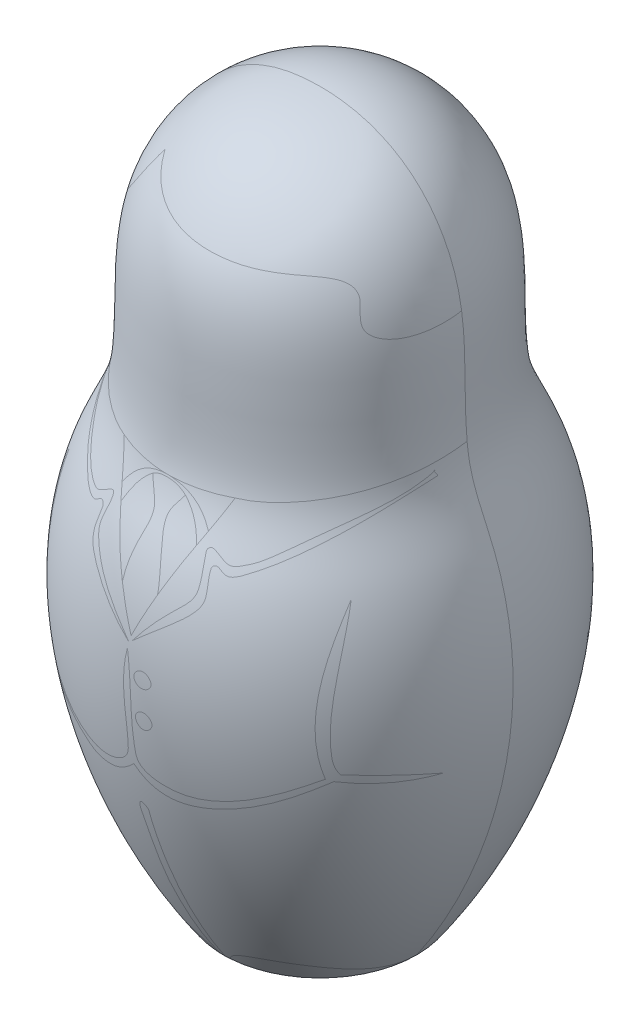
SolidWorks part; units mm, degrees
ref_plane "Plan de face" through (0, 0, 0) normal (0, 0, 1) x (1, 0, 0)
ref_plane "Plan de dessus" through (0, 0, 0) normal (0, 1, 0) x (1, 0, 0)
ref_plane "Plan de droite" through (0, 0, 0) normal (1, 0, 0) x (0, 0, -1)
sketch "Esquisse1" plane through (0, 0, 0) normal (0, 0, 1) x (1, 0, 0)
  line L0 (129.3492, 447.0549) -> (1494.8504, 447.0549) construction
  line L1 (0, 0) -> (0, 471.5) construction
  line L2 (0, 0) -> (-150.0296, 0) construction
  line L3 (0, 0) -> (0, 471.5)
  line L4 (0, 471.5) -> (-60.3699, 471.5) construction
  spline S0 degree 3 poles (0, 0) (-21.7271, 0) (-42.9654, 1.2949) (-63.75, 8) knots 0 0 0 0 1 1 1 1
  spline S1 degree 3 poles (-63.75, 8) (-110.6212, 75.097) (-153.2976, 197.1961) (-99.027, 296.1163) (-93.8746, 343.1344) (-100.8408, 417.717) (-51.4988, 471.5) (0, 471.5) knots 0 0 0 0 0.516513 0.585577 0.634733 0.784867 1 1 1 1
  dimension "D1" = 471.5
  dimension "D2" = 180.75
  dimension "D3" = 192.5
  dimension "D4" = 200
  dimension "D5" = 227.5
  dimension "D6" = 251
  dimension "D7" = 127.5
  dimension "D8" = 73
  dimension "D9" = 2
  dimension "D10" = 8
  dimension "D11" = 166
  dimension "D12" = 266.5
  dimension "D13" = 300
  dimension "D14" = 325.5
  dimension "D15" = 404
revolve "Révolution1" add sketch "Esquisse1" angle 360 about L3
ref_plane "Plan1" through (0, 0, 127) normal (0, 0, 1) x (1, 0, 0)
split line "Ligne de séparation3"
sketch "Esquisse3" plane through (0, 0, 127) normal (0, 0, 1) x (1, 0, 0)
  line L0 (129.3333, 447) -> (1494.6667, 447) construction
sketch3d "Esquisse3D3"
  arc A0 (63.75, 8, 0) -> (-63.75, 8, 0) centre (0, 8, 0) ccw construction
  arc A1 (63.75, 8, 0) -> (-63.75, 8, 0) centre (0, 8, 0) ccw construction
  arc A3 (63.75, 8, 0) -> (-63.75, 8, 0) centre (0, 8, 0) ccw construction
  point P0 (-63.75, 8, 0)
  point P1 (-96.5924, 320.5694, 0)
  point P2 (2.1214, 219.2703, 125.7318)
  point P3 (96.8721, 317.4915, 0)
  point P4 (-34.896, 21.9314, 64.092)
  point P5 (-3.421, 8, 63.6581)
  point P6 (4.545, 8, 63.5878)
  point P10 (0, -55.75, 0)
  point P11 (22.5504, 20.4053, 68.3902)
  point P15 (0, -55.75, 0)
  point P16 (47.011, 20.9144, 54.9755)
  point P17 (0.2994, 121.5679, 116.8557)
  point P18 (63.75, 8, 0)
  point P19 (63.75, 8, 0)
  point P20 (0, 471.5, 0)
  point P21 (-63.75, 8, 0)
  point P22 (0, 471.5, 0)
  point P23 (3.0312, 118.8634, 116.071)
  point P24 (3.0501, 97.6958, 109.3976)
  point P25 (1.0881, 8, 63.7407)
  point P29 (0, -55.75, 0)
  point P30 (10.0561, 182.4435, 126.4628)
  point P31 (-1.9324, 8, 63.7207)
  point P32 (-3.027, 55.1714, 91.4879)
  point P33 (-2.1547, 120.0749, 116.4276)
  point P34 (-1.1624, 121.5882, 116.8558)
  point P35 (15.0074, 177.836, 125.6951)
  point P36 (9.4058, 205.7294, 126.5297)
  point P37 (14.9379, 200.5466, 126.2001)
  point P38 (9.4931, 196.0044, 126.8041)
  point P39 (4.3686, 200.5757, 127.0052)
  point P40 (9.2308, 172.1282, 125.7929)
  point P41 (4.8984, 177.8704, 126.4954)
  point P42 (-35.9744, 301.2891, 92.9311)
  point P43 (1.0637, 221.52, 125.4694)
  point P44 (36.7481, 301.3439, 92.6125)
  point P45 (32.1198, 254.5054, 113.7083)
  point P46 (-72.4286, 286.5685, 75.8176)
  point P47 (-48.3809, 271.6775, 100.4855)
  point P48 (-43.1357, 271.6331, 102.8677)
  point P49 (-31.5697, 277.1148, 104.4017)
  point P50 (-31.0007, 274.5668, 105.7802)
  point P51 (-33.4455, 257.9423, 112.1193)
  point P52 (-0.2086, 217.8373, 125.9117)
  point P53 (-96.1025, 306.9029, 21.0637)
  point P54 (31.0306, 275.6136, 105.2762)
  point P55 (-34.9169, 249.4975, 114.492)
  point P56 (-37.0738, 256.8402, 111.3728)
  point P57 (-35.7203, 268.5841, 107.0736)
  point P58 (-37.4321, 269.8978, 105.8866)
  point P59 (-42.0501, 267.5888, 105.2041)
  point P60 (-50.3305, 267.6685, 101.4661)
  point P61 (32.9944, 276.9354, 104.046)
  point P62 (43.9841, 271.3084, 102.6642)
  point P63 (49.4223, 272.5547, 99.5414)
  point P64 (95.6123, 310.2258, 20.5768)
  point P65 (96.5144, 307.1724, 18.8202)
  point P66 (76.0684, 285.9788, 72.5308)
  point P67 (-95.7627, 308.1062, 21.5604)
  point P68 (48.0665, 267.0958, 102.8228)
  point P69 (42.7328, 266.8377, 105.2673)
  point P70 (36.969, 269.5906, 106.1905)
  point P71 (35.7797, 268.5972, 107.0479)
  point P72 (36.9226, 256.2794, 111.6232)
  point P73 (-0.5316, 214.1387, 126.2817)
  point P74 (-2.9218, 152.4546, 123.5713)
  point P75 (-19.5628, 140.5771, 119.8137)
  point P76 (-36.8841, 140.7008, 115.6883)
  point P77 (-91.5548, 164.8891, 85.6471)
  point P78 (-88.4673, 188.3172, 91.2377)
  point P79 (-90.8697, 227.8129, 85.196)
  point P80 (-90.8108, 257.9744, 73.7572)
  point P81 (-94.8912, 229.0429, 80.3789)
  point P82 (-93.1332, 198.5233, 86.5304)
  point P83 (-94.2344, 169.677, 83.4845)
  point P84 (-118.1077, 158.7426, 39.5987)
  point P85 (-94.1807, 163.7553, 82.5428)
  point P86 (-107.1053, 160.578, 64.1034)
  point P87 (19.9549, 134.8812, 118.4994)
  point P88 (36.5383, 135.6973, 114.6707)
  point P89 (92.9702, 163.2971, 83.8192)
  point P90 (-34.2098, 134.8647, 115.1916)
  point P91 (-31.9633, 134.3334, 115.7098)
  point P92 (-0.0302, 146.4869, 122.56)
  point P93 (104.7576, 160.131, 67.7606)
  point P94 (118.7156, 157.8779, 37.3259)
  point P95 (107.0656, 164.6096, 65.1636)
  point P96 (95.3607, 167.4122, 81.831)
  point P97 (93.3611, 176.9477, 85.3951)
  point P98 (93.708, 209.643, 85.1902)
  point P99 (91.7691, 260.4043, 71.1524)
  point P100 (88.6538, 210.467, 90.3559)
  point P101 (90.397, 164.9225, 86.8739)
  point P102 (38.2347, 141.3961, 115.3991)
  point P103 (19.7174, 141.378, 119.9549)
  point P104 (2.8199, 151.9842, 123.4958)
  point P105 (2.0868, 194.6854, 127.1473)
split line "Ligne de séparation8"
sketch3d "Esquisse3D4"
  point P0 (-24.3333, 276.1453, 106.7746)
  point P1 (-10.0408, 296.0562, 100.7119)
  point P3 (28.8345, 283.3201, 102.2791)
  point P4 (-35.9744, 301.2891, 92.9311)
  point P5 (1.0637, 221.52, 125.4694)
  point P6 (-35.9744, 301.2891, 92.9311)
  point P7 (1.0637, 221.52, 125.4694)
  point P8 (0.3697, 298.7748, 100.3528)
  point P9 (12.8279, 294.4565, 100.948)
  point P10 (25.36, 275.6775, 106.7542)
  point P11 (1.0637, 221.52, 125.4694)
  point P12 (36.7481, 301.3439, 92.6125)
  point P13 (16.1927, 295.7113, 100.0246)
  point P14 (36.7481, 301.3439, 92.6125)
  point P15 (-35.9744, 301.2891, 92.9311)
  point P16 (1.0637, 221.52, 125.4694)
  point P17 (36.7481, 301.3439, 92.6125)
  point P18 (0.1529, 299.9921, 100.0021)
  point P19 (0.1529, 299.9921, 100.0021)
  point P20 (96.8721, 317.4915, 0)
  point P22 (-27.7933, 283.4269, 102.5179)
  point P28 (-13.7117, 296.9571, 99.9803)
  point P29 (-35.9744, 301.2891, 92.9311)
  point P30 (1.0637, 221.52, 125.4694)
  point P42 (36.7481, 301.3439, 92.6125)
  point P43 (1.0637, 221.52, 125.4694)
  point P44 (36.7481, 301.3439, 92.6125)
  point P46 (-96.5924, 320.5694, 0)
  point P47 (-35.9744, 301.2891, 92.9311)
split line "Ligne de séparation10"
sketch3d "Esquisse3D7"
  point P0 (-9.4228, 296.4709, 100.6339)
  point P1 (-3.0237, 283.7652, 106.026)
  point P2 (-24.3333, 276.1453, 106.7746)
  point P3 (25.36, 275.6775, 106.7542)
  point P4 (-5.3866, 268.2959, 112.8691)
  point P5 (-9.4767, 244.6018, 120.6732)
  point P6 (-24.3333, 276.1453, 106.7746)
  point P7 (1.0637, 221.52, 125.4694)
  point P9 (12.2639, 294.8865, 100.8665)
  point P10 (5.7272, 283.1667, 106.1796)
  point P11 (-24.3333, 276.1453, 106.7746)
  point P12 (25.36, 275.6775, 106.7542)
  point P13 (8.2931, 268.4257, 112.6374)
  point P14 (12.577, 247.4651, 119.6164)
  point P15 (1.0637, 221.52, 125.4694)
  point P16 (25.36, 275.6775, 106.7542)
split line "Ligne de séparation25"
sketch3d "Esquisse3D9"
  point P0 (-93.3014, 389.9194, 0)
  point P1 (-61.3149, 417.4755, 59.8197)
  point P2 (-47.1291, 439.5681, 54.8639)
  point P3 (21.5578, 422.7832, 80.3424)
  point P4 (56.0605, 422.1872, 61.8586)
  point P5 (75.3166, 406.2353, 48.7845)
  point P6 (78.924, 394.5616, 48.2907)
  point P7 (85.089, 389.0231, 38.5943)
  point P8 (93.253, 390.2404, 0)
  point P9 (96.8721, 317.4915, 0)
  point P10 (0, 471.5, 0)
split line "Ligne de séparation28"
